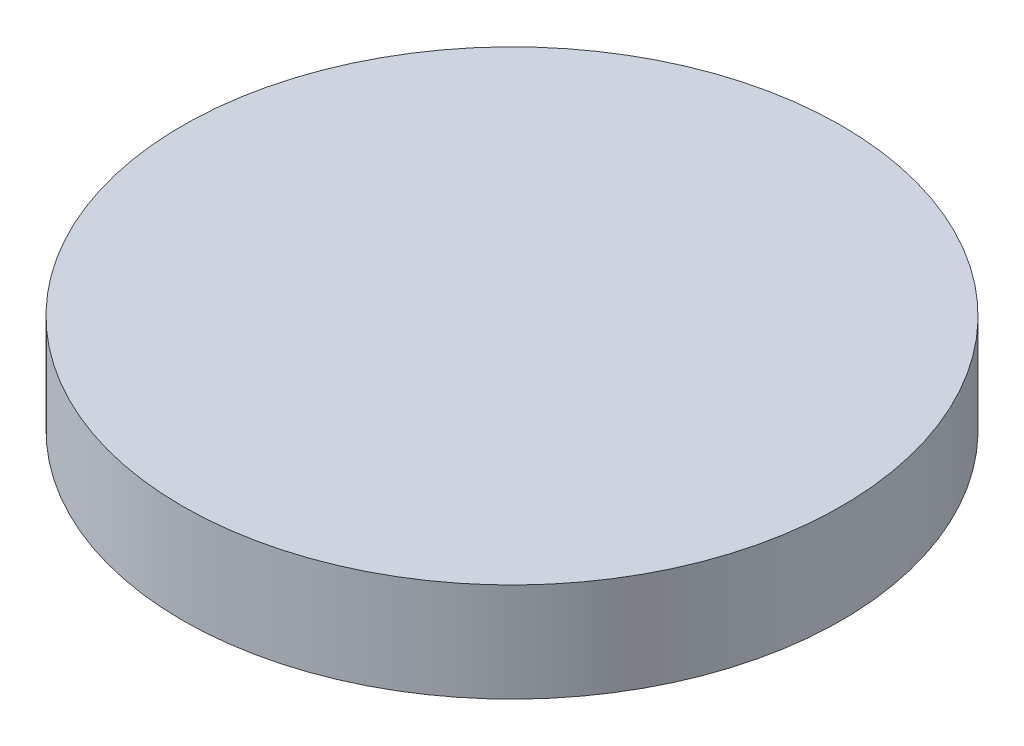
SolidWorks part; units mm, degrees
ref_plane "前视基准面" through (0, 0, 0) normal (0, 0, 1) x (1, 0, 0)
ref_plane "上视基准面" through (0, 0, 0) normal (0, 1, 0) x (1, 0, 0)
ref_plane "右视基准面" through (0, 0, 0) normal (1, 0, 0) x (0, 0, -1)
sketch "草图1" plane through (0, 0, 0) normal (0, 1, 0) x (1, 0, 0)
  circle A0 centre (0, 0) radius 5
  dimension "D1" = 10
extrude "凸台-拉伸1" add sketch "草图1" along normal blind 1.5
